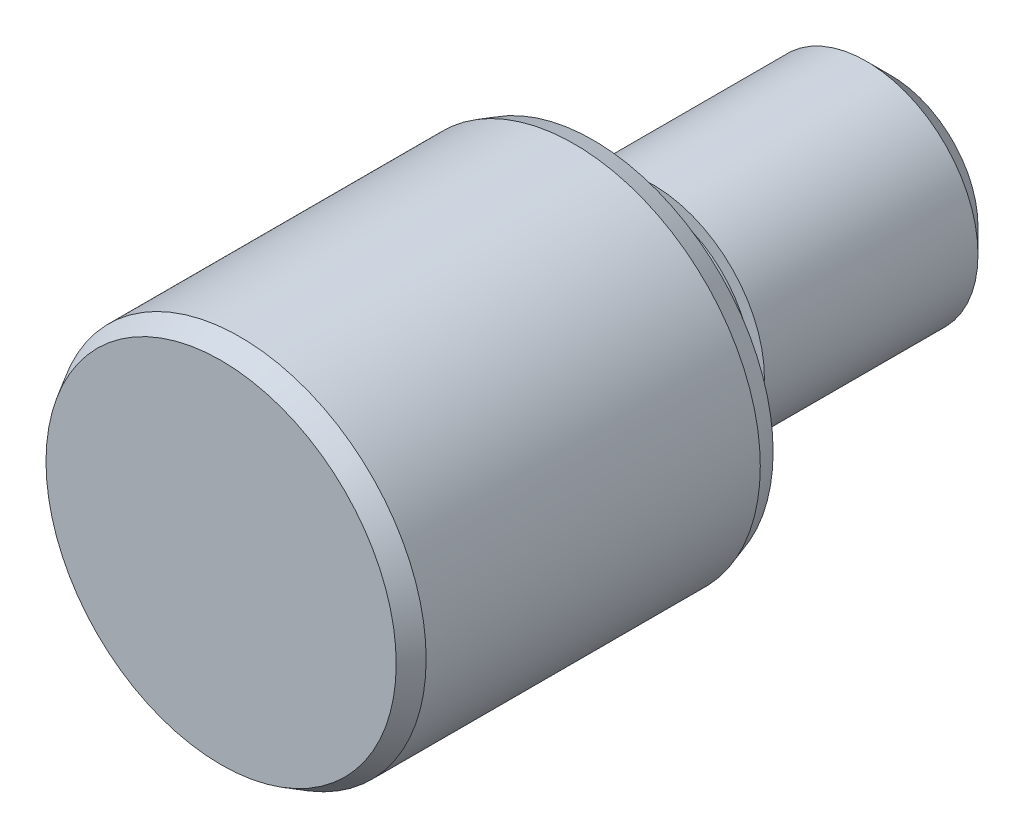
SolidWorks part; units mm, degrees
ref_plane "Front" through (0, 0, 0) normal (0, 0, 1) x (1, 0, 0)
ref_plane "Top" through (0, 0, 0) normal (0, 1, 0) x (1, 0, 0)
ref_plane "Right" through (0, 0, 0) normal (1, 0, 0) x (0, 0, -1)
sketch "Sketch1" plane through (0, 0, 0) normal (1, 0, 0) x (0, 0, -1)
  line L0 (-14.2875, 0) -> (14.2875, 0) construction
  line L1 (-14.2875, 0) -> (-14.2875, 7.9375)
  line L2 (-14.2875, 7.9375) -> (1.5875, 7.9375)
  line L3 (1.5875, 7.9375) -> (1.5875, 4.2148)
  line L4 (1.5875, 4.2148) -> (4.1275, 4.2148) construction
  line L5 (4.1275, 4.2148) -> (4.1275, 4.7625) construction
  line L6 (4.1275, 4.7625) -> (14.2875, 4.7625)
  line L7 (14.2875, 4.7625) -> (14.2875, 0)
  line L8 (14.2875, 0) -> (-14.2875, 0)
  line L9 (1.5875, 4.2148) -> (3.5798, 4.2148)
  line L10 (3.5798, 4.2148) -> (4.1275, 4.7625)
  dimension "Diameter" = 15.875
  dimension "Length" = 15.875
  dimension "Stud Length" = 12.7
  dimension "Stud Diameter" = 9.525
  dimension "Gap Ref" = 2.54
  dimension "Collar OD Ref" = 8.4296
  dimension "D3" = 45
sketch "Sketch2" plane through (0, 0, 0) normal (1, 0, 0) x (0, 0, -1)
  line L0 (4.1275, 4.7625) -> (4.1275, 4.2148)
  line L1 (4.1275, 4.2148) -> (3.5798, 4.2148)
  line L8 (-14.2875, 7.9375) -> (-14.2875, 0)
  line L9 (1.5875, 7.9375) -> (-14.2875, 7.9375)
  line L10 (1.5875, 4.2148) -> (1.5875, 7.9375)
  line L11 (3.5798, 4.2148) -> (1.5875, 4.2148)
  line L12 (4.1275, 4.7625) -> (3.5798, 4.2148)
  line L13 (14.2875, 4.7625) -> (4.1275, 4.7625)
  line L14 (14.2875, 0) -> (14.2875, 4.7625)
  line L15 (-14.2875, 0) -> (14.2875, 0)
  line L16 (-14.2875, 7.9375) -> (-14.2875, 0)
  line L17 (1.5875, 7.9375) -> (-14.2875, 7.9375)
  line L18 (1.5875, 4.2148) -> (1.5875, 7.9375)
  line L19 (3.5798, 4.2148) -> (1.5875, 4.2148)
  line L20 (4.1275, 4.7625) -> (3.5798, 4.2148) construction
  line L21 (14.2875, 4.7625) -> (4.1275, 4.7625)
  line L22 (14.2875, 0) -> (14.2875, 4.7625)
  line L23 (-14.2875, 0) -> (14.2875, 0)
  dimension "D1" = 0
revolve "Revolve2" add sketch "Sketch2" angle 360 about L23
chamfer "Chamfer1" distance 0.8096 angle 30 1 edges at (7.9375, 0, 14.2875)
chamfer "Chamfer2" distance 1.0478 angle 45 1 edges at (4.7625, 0, -14.2875)
fillet "Fillet1" radius 0.1905 1 edges at (4.2148, 0, -1.5875)
chamfer "Chamfer4" distance 0.8096 angle 18 1 edges at (7.9375, 0, -1.5875)
equation "\"D1@Chamfer2\"=\"Stud Diameter@Sketch1\" * .11"
equation "\"D1@Fillet1\"=\"Gap Ref@Sketch1\" * 0.075"
equation "\"D1@Chamfer4\"=\"Chamfer@Chamfer1\" "
